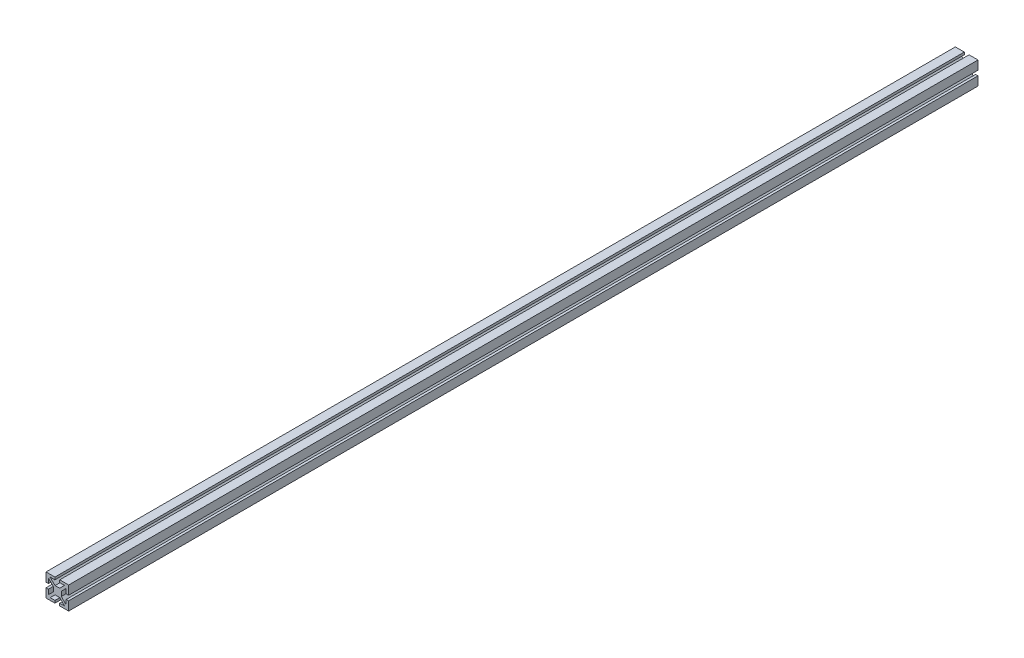
SolidWorks part; units mm, degrees
ref_plane "Front Plane" through (0, 0, 0) normal (0, 0, 1) x (1, 0, 0)
ref_plane "Top Plane" through (0, 0, 0) normal (0, 1, 0) x (1, 0, 0)
ref_plane "Right Plane" through (0, 0, 0) normal (1, 0, 0) x (0, 0, -1)
sketch "Sketch2" plane through (0.5947, -0.5947, 0) normal (0, 0, 1) x (1, 0, 0)
  line L0 (-0.5947, 0.5947) -> (-0.5947, 20.2394) construction
  line L1 (-0.5947, 0.5947) -> (-20.2394, 0.5947) construction
  line L2 (-0.5947, 0.5947) -> (-20.2394, 20.2394) construction
  line L3 (-19.6447, 19.6447) -> (-4.6587, 19.6447)
  line L4 (-4.6587, 19.6447) -> (-4.6587, 15.5807)
  line L5 (-4.6587, 15.5807) -> (-12.707, 15.5807)
  line L6 (-12.707, 15.5807) -> (-4.4774, 7.3511)
  line L7 (-4.4774, 7.3511) -> (3.288, 7.3511)
  line L8 (-19.6447, 19.6447) -> (-19.6447, 4.6587)
  line L9 (-19.6447, 4.6587) -> (-15.5807, 4.6587)
  line L10 (-15.5807, 4.6587) -> (-15.5807, 12.707)
  line L11 (-15.5807, 12.707) -> (-7.3511, 4.4774)
  line L12 (-7.3511, 4.4774) -> (-7.3511, -3.288)
  line L13 (-4.4774, -6.1617) -> (3.288, -6.1617)
  line L14 (-12.707, -14.3913) -> (-4.4774, -6.1617)
  line L15 (-4.6587, -14.3913) -> (-12.707, -14.3913)
  line L16 (-4.6587, -18.4553) -> (-4.6587, -14.3913)
  line L17 (-19.6447, -18.4553) -> (-4.6587, -18.4553)
  line L18 (-19.6447, -18.4553) -> (-19.6447, -3.4693)
  line L19 (-19.6447, -3.4693) -> (-15.5807, -3.4693)
  line L20 (-15.5807, -3.4693) -> (-15.5807, -11.5176)
  line L21 (-15.5807, -11.5176) -> (-7.3511, -3.288)
  line L22 (11.5176, 15.5807) -> (3.288, 7.3511)
  line L23 (3.4693, 15.5807) -> (11.5176, 15.5807)
  line L24 (3.4693, 19.6447) -> (3.4693, 15.5807)
  line L25 (18.4553, 19.6447) -> (3.4693, 19.6447)
  line L26 (18.4553, 19.6447) -> (18.4553, 4.6587)
  line L27 (18.4553, 4.6587) -> (14.3913, 4.6587)
  line L28 (14.3913, 4.6587) -> (14.3913, 12.707)
  line L29 (14.3913, 12.707) -> (6.1617, 4.4774)
  line L30 (6.1617, 4.4774) -> (6.1617, -3.288)
  line L31 (14.3913, -11.5176) -> (6.1617, -3.288)
  line L32 (14.3913, -3.4693) -> (14.3913, -11.5176)
  line L33 (18.4553, -3.4693) -> (14.3913, -3.4693)
  line L34 (18.4553, -18.4553) -> (18.4553, -3.4693)
  line L35 (18.4553, -18.4553) -> (3.4693, -18.4553)
  line L36 (3.4693, -18.4553) -> (3.4693, -14.3913)
  line L37 (3.4693, -14.3913) -> (11.5176, -14.3913)
  line L38 (11.5176, -14.3913) -> (3.288, -6.1617)
  point P26 (-7.3511, 0.5947)
  point P27 (-0.5947, 7.3511)
  point P44 (-0.5947, -6.1617)
  dimension "D1" = 38.1
  dimension "D2" = 8.128
  dimension "D3" = 13.5128
  dimension "D4" = 4.064
  dimension "D5" = 4.064
extrude "Boss-Extrude1" add sketch "Sketch2" along normal up to surface (1531.1438 mm away)
other "1515<1>"
